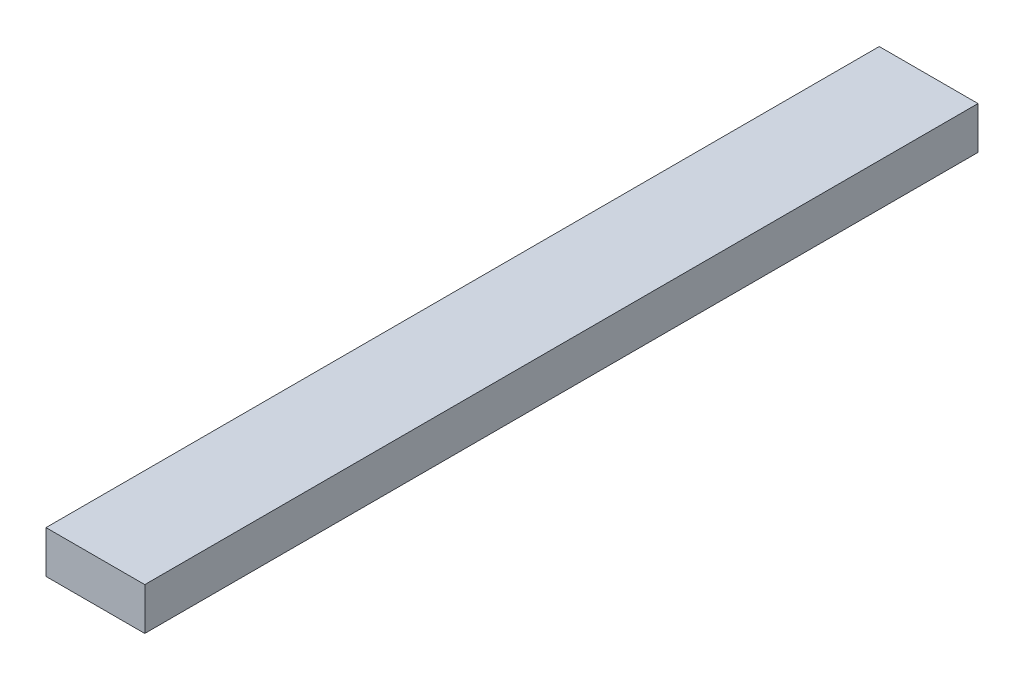
SolidWorks part; units mm, degrees
material "Pine"
ref_plane "Front Plane" through (0, 0, 0) normal (0, 0, 1) x (1, 0, 0)
ref_plane "Top Plane" through (0, 0, 0) normal (0, 1, 0) x (1, 0, 0)
ref_plane "Right Plane" through (0, 0, 0) normal (1, 0, 0) x (0, 0, -1)
sketch "Sketch1" plane through (0, 0, 0) normal (0, 0, 1) x (1, 0, 0)
  line L1 (-44.45, -19.05) -> (44.45, -19.05)
  line L2 (-44.45, -19.05) -> (-44.45, 19.05)
  line L3 (-44.45, 19.05) -> (44.45, 19.05)
  line L4 (44.45, -19.05) -> (44.45, 19.05)
  line L5 (-44.45, -19.05) -> (44.45, 19.05) construction
  line L6 (-44.45, 19.05) -> (44.45, -19.05) construction
  point P0 (0, 0)
  dimension "D1" = 88.9
  dimension "D2" = 38.1
extrude "Boss-Extrude1" add sketch "Sketch1" along normal blind 750
